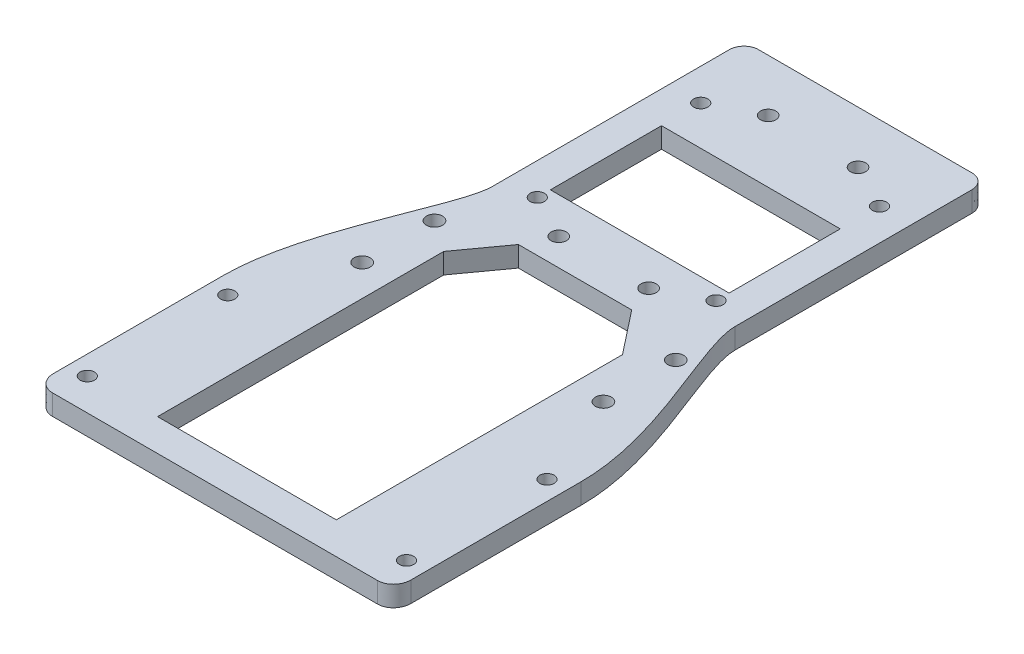
SolidWorks part; units mm, degrees
material "Acrylic (Medium-high impact)"
ref_plane "Front Plane" through (0, 0, 0) normal (0, 0, 1) x (1, 0, 0)
ref_plane "Top Plane" through (0, 0, 0) normal (0, 1, 0) x (1, 0, 0)
ref_plane "Right Plane" through (0, 0, 0) normal (1, 0, 0) x (0, 0, -1)
sketch "Sketch1" plane through (0, 0, 0) normal (0, 1, 0) x (1, 0, 0)
  line L0 (-201.6127, -11.6994) -> (-201.6127, 47.1689)
  line L1 (-197.9814, 50.8) -> (-144.919, 50.8)
  line L2 (-141.2875, 47.1689) -> (-141.2875, -11.6994)
  line L3 (-127, -64.3399) -> (-127, -106.6381)
  line L4 (-131.0204, -110.8894) -> (-211.8792, -110.8894)
  line L5 (-215.9, -106.6381) -> (-215.9, -64.3399)
  line L6 (-193.675, -102.9519) -> (-193.675, -31.7898)
  line L7 (-193.675, -31.7898) -> (-185.8803, -21.0221)
  line L8 (-185.8803, -21.0221) -> (-157.6989, -21.0221)
  line L9 (-157.6989, -21.0221) -> (-149.225, -31.7898)
  line L10 (-149.225, -31.7898) -> (-149.225, -102.9519)
  line L11 (-149.225, -102.9519) -> (-193.675, -102.9519)
  line L12 (-149.225, -5.2753) -> (-193.675, -5.2753)
  line L13 (-193.675, -5.2753) -> (-193.675, 22.3602)
  line L14 (-193.675, 22.3602) -> (-149.225, 22.3602)
  line L15 (-149.225, 22.3602) -> (-149.225, -5.2753)
  circle A0 centre (-201.4475, -44.3094) radius 2.0003
  circle A1 centre (-141.4529, -44.3094) radius 2.0003
  circle A2 centre (-141.4529, -26.3259) radius 2.0002
  circle A3 centre (-193.675, -8.5244) radius 1.7778
  circle A4 centre (-160.2741, -14.2394) radius 1.9048
  circle A5 centre (-149.225, -8.5244) radius 1.7777
  circle A6 centre (-193.6749, 32.1157) radius 1.7779
  circle A7 centre (-182.6261, 37.8308) radius 1.905
  circle A8 centre (-160.2739, 37.8308) radius 1.905
  circle A9 centre (-149.225, 32.1157) radius 1.7777
  circle A10 centre (-182.6261, -14.2394) radius 1.905
  circle A11 centre (-201.4475, -26.3259) radius 2.0002
  circle A12 centre (-211.1375, -68.0265) radius 1.778
  circle A13 centre (-131.7625, -102.9515) radius 1.778
  circle A14 centre (-211.1375, -102.9515) radius 1.778
  circle A15 centre (-131.7625, -68.0265) radius 1.778
  spline S0 degree 3 poles (-201.6127, 47.1689) (-201.6127, 49.1744) (-199.9869, 50.8) (-197.9814, 50.8) knots 1 1 1 1 2 2 2 2
  spline S1 degree 3 poles (-144.919, 50.8) (-142.9136, 50.8) (-141.2875, 49.1744) (-141.2875, 47.1689) knots 3 3 3 3 4 4 4 4
  spline S2 degree 3 poles (-141.2875, -11.6994) (-141.2875, -20.4162) (-127, -44.167) (-127, -64.3399) knots 5 5 5 5 6 6 6 6
  spline S3 degree 3 poles (-127, -106.6381) (-127, -108.9863) (-128.8001, -110.8894) (-131.0204, -110.8894) knots 7 7 7 7 8 8 8 8
  spline S4 degree 3 poles (-211.8792, -110.8894) (-214.0998, -110.8894) (-215.9, -108.9863) (-215.9, -106.6381) knots 9 9 9 9 10 10 10 10
  spline S5 degree 3 poles (-215.9, -64.3399) (-215.9, -44.167) (-201.6127, -20.4162) (-201.6127, -11.6994) knots 11 11 11 11 12 12 12 12
  point P22 (0, 0)
  point P55 (0, 0)
  point P56 (0, 0)
  point P57 (0, 0)
  spline B0 degree 3 poles (-184.531, 37.8308) (-184.531, 38.8829) (-183.678, 39.7357) (-182.6262, 39.7357) (-181.5741, 39.7357) (-180.7211, 38.8829) (-180.7211, 37.8308) knots 2 2 2 2 3 3 3 4 4 4 4
  spline B1 degree 3 poles (-180.7211, 37.8308) (-180.7211, 36.7788) (-181.5741, 35.9258) (-182.6262, 35.9258) (-183.678, 35.9258) (-184.531, 36.7788) (-184.531, 37.8308) knots 0 0 0 0 1 1 1 2 2 2 2
  spline B2 degree 3 poles (-162.1789, 37.8308) (-162.1789, 38.8829) (-161.3259, 39.7357) (-160.2741, 39.7357) (-159.222, 39.7357) (-158.369, 38.8829) (-158.369, 37.8308) knots 2 2 2 2 3 3 3 4 4 4 4
  spline B3 degree 3 poles (-158.369, 37.8308) (-158.369, 36.7788) (-159.222, 35.9258) (-160.2741, 35.9258) (-161.3259, 35.9258) (-162.1789, 36.7788) (-162.1789, 37.8308) knots 0 0 0 0 1 1 1 2 2 2 2
  spline B4 degree 3 poles (-184.531, -14.2394) (-184.531, -13.1873) (-183.678, -12.3346) (-182.6262, -12.3346) (-181.5741, -12.3346) (-180.7211, -13.1873) (-180.7211, -14.2394) knots 2 2 2 2 3 3 3 4 4 4 4
  spline B5 degree 3 poles (-180.7211, -14.2394) (-180.7211, -15.2912) (-181.5741, -16.1442) (-182.6262, -16.1442) (-183.678, -16.1442) (-184.531, -15.2912) (-184.531, -14.2394) knots 0 0 0 0 1 1 1 2 2 2 2
  spline B6 degree 3 poles (-162.1789, -14.2394) (-162.1789, -13.1873) (-161.3259, -12.3346) (-160.2745, -12.3346) (-159.2223, -12.3346) (-158.3693, -13.1873) (-158.3693, -14.2394) knots 2 2 2 2 3 3 3 4 4 4 4
  spline B7 degree 3 poles (-158.3693, -14.2394) (-158.3693, -15.2912) (-159.2223, -16.1442) (-160.2745, -16.1442) (-161.3259, -16.1442) (-162.1789, -15.2912) (-162.1789, -14.2394) knots 0 0 0 0 1 1 1 2 2 2 2
  spline B8 degree 3 poles (-131.7625, -66.2485) (-130.7806, -66.2485) (-129.9845, -67.045) (-129.9845, -68.0269) (-129.9845, -69.0087) (-130.7806, -69.8045) (-131.7625, -69.8045) knots 2 2 2 2 3 3 3 4 4 4 4
  spline B9 degree 3 poles (-131.7625, -69.8045) (-132.7444, -69.8045) (-133.5405, -69.0087) (-133.5405, -68.0269) (-133.5405, -67.045) (-132.7444, -66.2485) (-131.7625, -66.2485) knots 0 0 0 0 1 1 1 2 2 2 2
  spline B10 degree 3 poles (-131.7625, -101.1735) (-130.7806, -101.1735) (-129.9845, -101.97) (-129.9845, -102.9519) (-129.9845, -103.9337) (-130.7806, -104.7295) (-131.7625, -104.7295) knots 2 2 2 2 3 3 3 4 4 4 4
  spline B11 degree 3 poles (-131.7625, -104.7295) (-132.7444, -104.7295) (-133.5405, -103.9337) (-133.5405, -102.9519) (-133.5405, -101.97) (-132.7444, -101.1735) (-131.7625, -101.1735) knots 0 0 0 0 1 1 1 2 2 2 2
  spline B12 degree 3 poles (-211.1375, -66.2485) (-210.1555, -66.2485) (-209.3595, -67.045) (-209.3595, -68.0269) (-209.3595, -69.0087) (-210.1555, -69.8045) (-211.1375, -69.8045) knots 2 2 2 2 3 3 3 4 4 4 4
  spline B13 degree 3 poles (-211.1375, -69.8045) (-212.1195, -69.8045) (-212.9155, -69.0087) (-212.9155, -68.0269) (-212.9155, -67.045) (-212.1195, -66.2485) (-211.1375, -66.2485) knots 0 0 0 0 1 1 1 2 2 2 2
  spline B14 degree 3 poles (-211.1375, -101.1735) (-210.1555, -101.1735) (-209.3595, -101.97) (-209.3595, -102.9519) (-209.3595, -103.9337) (-210.1555, -104.7295) (-211.1375, -104.7295) knots 2 2 2 2 3 3 3 4 4 4 4
  spline B15 degree 3 poles (-211.1375, -104.7295) (-212.1195, -104.7295) (-212.9155, -103.9337) (-212.9155, -102.9519) (-212.9155, -101.97) (-212.1195, -101.1735) (-211.1375, -101.1735) knots 0 0 0 0 1 1 1 2 2 2 2
  spline B16 degree 3 poles (-201.4475, -46.3097) (-202.5523, -46.3097) (-203.4477, -45.4139) (-203.4477, -44.3093) (-203.4477, -43.2044) (-202.5523, -42.309) (-201.4475, -42.309) knots 2 2 2 2 3 3 3 4 4 4 4
  spline B17 degree 3 poles (-201.4475, -42.309) (-200.3426, -42.309) (-199.4473, -43.2044) (-199.4473, -44.3093) (-199.4473, -45.4139) (-200.3426, -46.3097) (-201.4475, -46.3097) knots 0 0 0 0 1 1 1 2 2 2 2
  spline B18 degree 3 poles (-201.4475, -28.3261) (-202.5523, -28.3261) (-203.4477, -27.4311) (-203.4477, -26.3259) (-203.4477, -25.2214) (-202.5523, -24.3256) (-201.4475, -24.3256) knots 2 2 2 2 3 3 3 4 4 4 4
  spline B19 degree 3 poles (-201.4475, -24.3256) (-200.3426, -24.3256) (-199.4473, -25.2214) (-199.4473, -26.3259) (-199.4473, -27.4311) (-200.3426, -28.3261) (-201.4475, -28.3261) knots 0 0 0 0 1 1 1 2 2 2 2
  spline B20 degree 3 poles (-141.4529, -46.3097) (-142.5574, -46.3097) (-143.4531, -45.4139) (-143.4531, -44.3093) (-143.4531, -43.2044) (-142.5574, -42.309) (-141.4529, -42.309) knots 2 2 2 2 3 3 3 4 4 4 4
  spline B21 degree 3 poles (-141.4529, -42.309) (-140.3477, -42.309) (-139.4526, -43.2044) (-139.4526, -44.3093) (-139.4526, -45.4139) (-140.3477, -46.3097) (-141.4529, -46.3097) knots 0 0 0 0 1 1 1 2 2 2 2
  spline B22 degree 3 poles (-141.4529, -28.3261) (-142.5574, -28.3261) (-143.4531, -27.4311) (-143.4531, -26.3259) (-143.4531, -25.2214) (-142.5574, -24.3256) (-141.4529, -24.3256) knots 2 2 2 2 3 3 3 4 4 4 4
  spline B23 degree 3 poles (-141.4529, -24.3256) (-140.3477, -24.3256) (-139.4526, -25.2214) (-139.4526, -26.3259) (-139.4526, -27.4311) (-140.3477, -28.3261) (-141.4529, -28.3261) knots 0 0 0 0 1 1 1 2 2 2 2
  spline B24 degree 3 poles (-195.4528, 32.1157) (-195.4528, 33.0975) (-194.6569, 33.8935) (-193.6748, 33.8935) (-192.693, 33.8935) (-191.897, 33.0975) (-191.897, 32.1157) knots 2 2 2 2 3 3 3 4 4 4 4
  spline B25 degree 3 poles (-191.897, 32.1157) (-191.897, 31.1337) (-192.693, 30.3377) (-193.6748, 30.3377) (-194.6569, 30.3377) (-195.4528, 31.1337) (-195.4528, 32.1157) knots 0 0 0 0 1 1 1 2 2 2 2
  spline B26 degree 3 poles (-151.0027, 32.1157) (-151.0027, 33.0975) (-150.2069, 33.8935) (-149.225, 33.8935) (-148.2431, 33.8935) (-147.4473, 33.0975) (-147.4473, 32.1157) knots 2 2 2 2 3 3 3 4 4 4 4
  spline B27 degree 3 poles (-147.4473, 32.1157) (-147.4473, 31.1337) (-148.2431, 30.3377) (-149.225, 30.3377) (-150.2069, 30.3377) (-151.0027, 31.1337) (-151.0027, 32.1157) knots 0 0 0 0 1 1 1 2 2 2 2
  spline B28 degree 3 poles (-195.4528, -8.5244) (-195.4528, -7.5425) (-194.6567, -6.7467) (-193.6748, -6.7467) (-192.693, -6.7467) (-191.8972, -7.5425) (-191.8972, -8.5244) knots 2 2 2 2 3 3 3 4 4 4 4
  spline B29 degree 3 poles (-191.8972, -8.5244) (-191.8972, -9.5062) (-192.693, -10.3024) (-193.6748, -10.3024) (-194.6567, -10.3024) (-195.4528, -9.5062) (-195.4528, -8.5244) knots 0 0 0 0 1 1 1 2 2 2 2
  spline B30 degree 3 poles (-151.0027, -8.5244) (-151.0027, -7.5425) (-150.2069, -6.7467) (-149.225, -6.7467) (-148.2431, -6.7467) (-147.4473, -7.5425) (-147.4473, -8.5244) knots 2 2 2 2 3 3 3 4 4 4 4
  spline B31 degree 3 poles (-147.4473, -8.5244) (-147.4473, -9.5062) (-148.2431, -10.3024) (-149.225, -10.3024) (-150.2069, -10.3024) (-151.0027, -9.5062) (-151.0027, -8.5244) knots 0 0 0 0 1 1 1 2 2 2 2
sketch_block_instance "BLOCK 2-1"
sketch_block "BLOCK 2"
sketch_block_instance "BLOCK 3-1"
sketch_block "BLOCK 3"
sketch_block_instance "BLOCK 4-1"
sketch_block "BLOCK 4"
sketch_block_instance "BLOCK 5-1"
sketch_block "BLOCK 5"
extrude "Boss-Extrude2" add sketch "Sketch1" along normal blind 5.08 contours L7 L8 L9 L10 L11 L6 | L13 L14 L15 L12 | L0 S0 L1 S1 L2 S2 L3 S3 L4 S4 L5 S5 | A11 | A10 | A3 | A4 | A7 | A8 | A9 | A5 | A2 | A0 | A1 | A15 | A13 | A14 | A12 | A6
